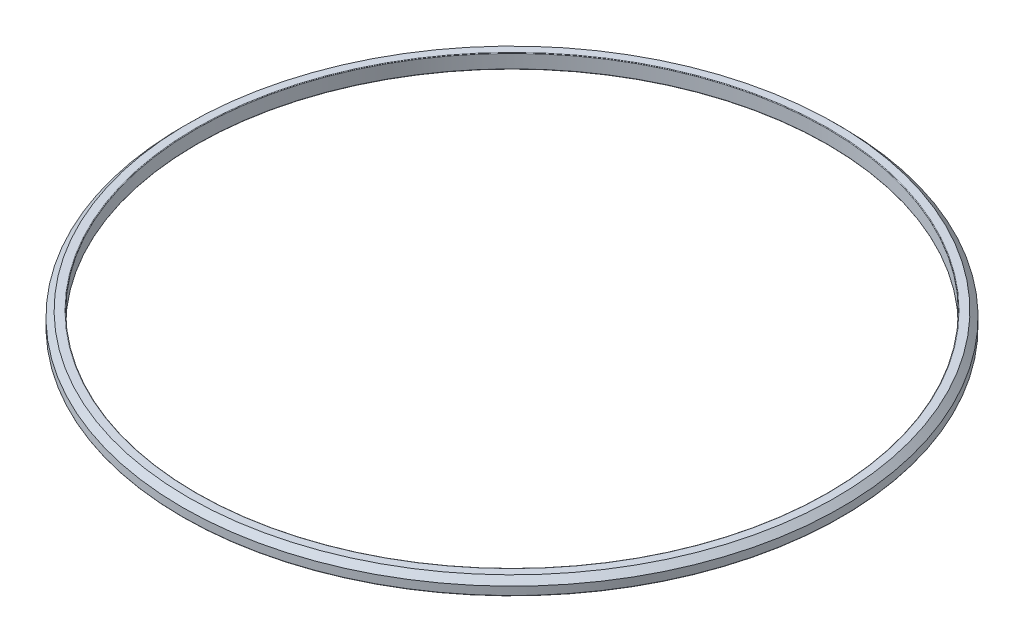
SolidWorks part; units mm, degrees
material "PETG"
ref_plane "Front Plane" through (0, 0, 0) normal (0, 0, 1) x (1, 0, 0)
ref_plane "Top Plane" through (0, 0, 0) normal (0, 1, 0) x (1, 0, 0)
ref_plane "Right Plane" through (0, 0, 0) normal (1, 0, 0) x (0, 0, -1)
sketch "Sketch1" plane through (0, 0, 0) normal (0, 1, 0) x (1, 0, 0)
  circle A0 centre (0, 0) radius 57.2125
  circle A1 centre (0, 0) radius 54.7875
  dimension "Ring OD" = 114.425
  dimension "Ring ID" = 109.575
extrude "Boss-Extrude1" add sketch "Sketch1" along normal blind 2.5
chamfer "Chamfer1" distance 1 angle 45 1 edges at (0, 2.5, 57.2125)
fillet "Fillet1" radius 0.1 3 edges at (0, 2.5, 54.7875) (0, 0, 54.7875) (0, 0, 57.2125)
equation "\"tol_dia_id_intfc\" = 0.0500mm ' For hole diameters - Interference fit"
equation "\"tol_dia_id_slip\"  = 0.0750mm ' For hole diameters - Slip fit"
equation "\"tol_dia_id_clear\" = 0.1000mm ' For hole diameters - Clearance fit"
equation "\"tol_dia_od_intfc\" = 0.0500mm ' For shaft diameters - Interference fit"
equation "\"tol_dia_od_slip\"  = 0.0750mm ' For shaft diameters - Slip fit"
equation "\"tol_dia_od_clear\" = 0.1000mm ' For shaft diameters - Clearance fit"
equation "\"tol_general_intfc\"= 0.0250mm ' For general parts (Horiz) - Interference fit"
equation "\"tol_general_slip\" = 0.0375mm ' For general parts (Horiz) - Slip fit"
equation "\"tol_general_clear\"= 0.0500mm ' For general parts (Horiz) - Clearance fit"
equation "\"tol_layer_intfc\"  = 0.0250mm ' For all parts (Vert) - Interference fit"
equation "\"tol_layer_slip\"   = 0.0375mm ' For all parts (Vert) - Slip fit"
equation "\"tol_layer_clear\"  = 0.0500mm ' For all parts (Vert) - Clearance fit"
equation "\"tol_corner_rad\"   = 0.100mm ' For corners that fit into other parts"
equation "\"Ring OD@Sketch1\"= 114.50mm - \"tol_dia_od_slip\""
equation "\"Ring ID@Sketch1\" = 114.5 - ( 2.5 * 2 ) + \"tol_dia_id_slip\""
equation "\"D1@Fillet1\"=\"tol_corner_rad\""
